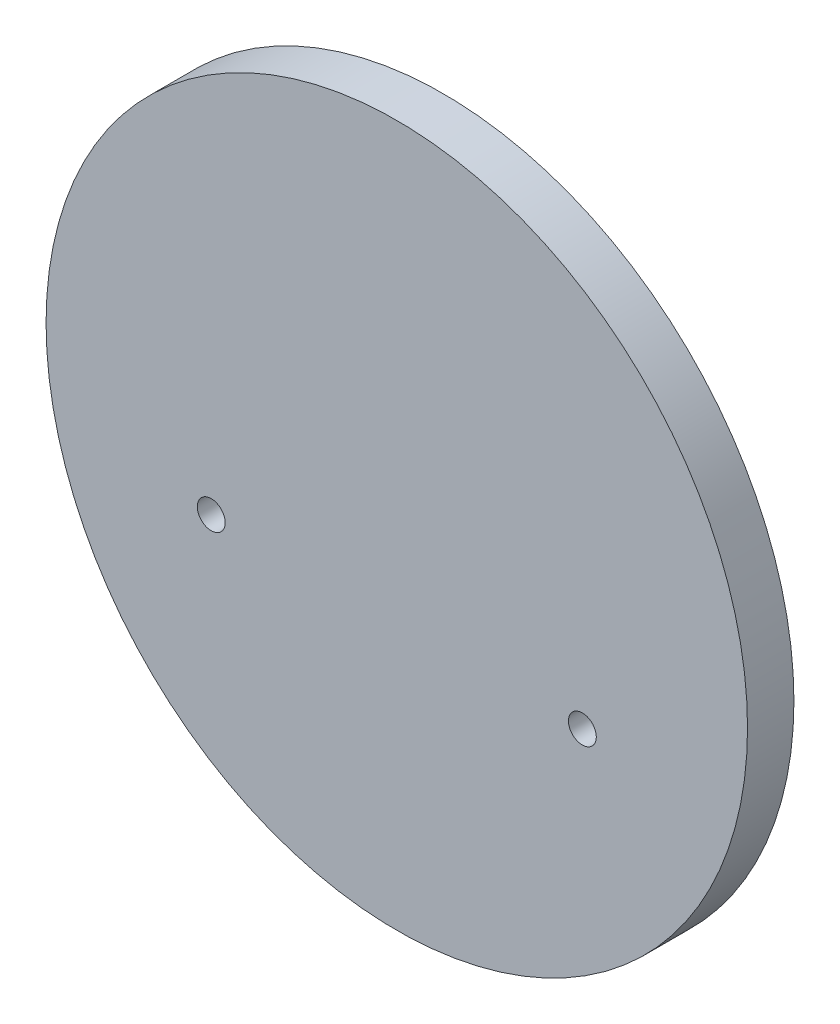
SolidWorks part; units mm, degrees
ref_plane "Front Plane" through (0, 0, 0) normal (0, 0, 1) x (1, 0, 0)
ref_plane "Top Plane" through (0, 0, 0) normal (0, 1, 0) x (1, 0, 0)
ref_plane "Right Plane" through (0, 0, 0) normal (1, 0, 0) x (0, 0, -1)
sketch "Sketch1" plane through (0, 0, 0) normal (0, 0, 1) x (1, 0, 0)
  line L0 (20, -9) -> (-20, -9) construction
  line L1 (0, -9) -> (0, 0) construction
  circle A0 centre (0, 0) radius 37.8
  circle A1 centre (-20, -9) radius 1.5
  circle A2 centre (20, -9) radius 1.5
  point P6 (0, -9)
  dimension "D1" = 75.6
  dimension "D2" = 3
  dimension "D3" = 3
  dimension "D4" = 9
  dimension "D5" = 40
extrude "Boss-Extrude1" add sketch "Sketch1" along normal blind 5
